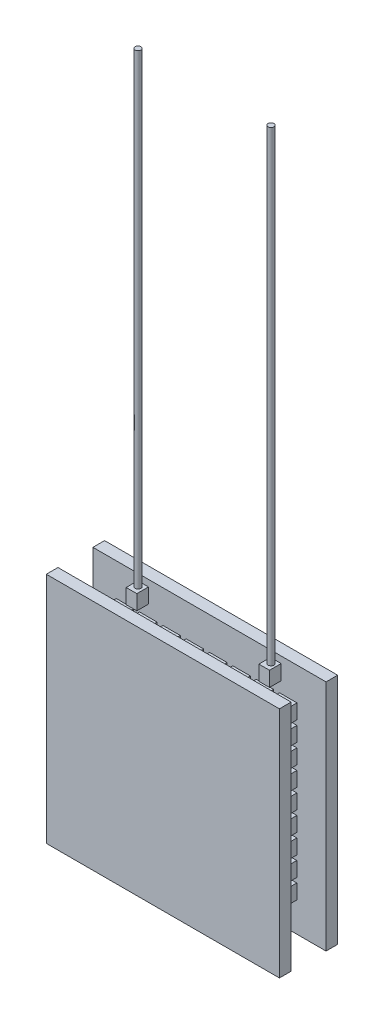
SolidWorks part; units mm, degrees
ref_plane "Front Plane" through (0, 0, 0) normal (0, 0, 1) x (1, 0, 0)
ref_plane "Top Plane" through (0, 0, 0) normal (0, 1, 0) x (1, 0, 0)
ref_plane "Right Plane" through (0, 0, 0) normal (1, 0, 0) x (0, 0, -1)
sketch "Sketch2" plane through (0, 0, 0) normal (0, 0, 1) x (1, 0, 0)
  line L0 (-3.25, 4) -> (-3.25, -4) construction
  line L1 (-5, 5) -> (5, 5)
  line L2 (-5, 5) -> (-5, -5)
  line L3 (-5, -5) -> (5, -5)
  line L4 (5, 5) -> (5, -5)
  line L5 (-5, 5) -> (5, -5) construction
  line L6 (-5, -5) -> (5, 5) construction
  line L7 (-4, 4) -> (4, 4)
  line L8 (-4, 4) -> (-4, -4)
  line L9 (-4, -4) -> (4, -4)
  line L10 (4, 4) -> (4, -4)
  line L11 (-4, 4) -> (4, -4) construction
  line L12 (-4, -4) -> (4, 4) construction
  line L13 (-3, 4) -> (-3, -4) construction
  line L14 (-2.25, 4) -> (-2.25, -4) construction
  line L15 (-2, 4) -> (-2, -4) construction
  line L16 (-1.25, 4) -> (-1.25, -4) construction
  line L17 (-1, 4) -> (-1, -4) construction
  line L18 (-0.25, 4) -> (-0.25, -4) construction
  line L19 (0, 4) -> (0, -4) construction
  line L20 (0.75, 4) -> (0.75, -4) construction
  line L21 (1, 4) -> (1, -4) construction
  line L22 (1.75, 4) -> (1.75, -4) construction
  line L23 (2, 4) -> (2, -4) construction
  line L24 (2.75, 4) -> (2.75, -4) construction
  line L25 (3, 4) -> (3, -4) construction
  line L26 (3.75, 4) -> (3.75, -4) construction
  line L27 (-4, 3.7306) -> (3.7306, 3.7306) construction
  line L28 (-4, 3.5986) -> (3.75, 3.5986) construction
  line L29 (-4, 2.7927) -> (3.75, 2.7927) construction
  line L30 (-4, 2.9681) -> (3.75, 2.9681) construction
  line L31 (-4, 2.1419) -> (3.75, 2.1419) construction
  line L32 (-4, 1.9812) -> (3.75, 1.9812) construction
  line L33 (-4, 1.3998) -> (3.75, 1.3998) construction
  line L34 (-4, 1.2019) -> (3.75, 1.2019) construction
  line L35 (-4, 0.6083) -> (3.75, 0.6083) construction
  line L36 (-4, 0.4475) -> (3.75, 0.4475) construction
  line L37 (-4, 0.3462) -> (3.75, 0.3462) construction
  line L38 (-4, -0.2996) -> (3.75, -0.2996) construction
  line L39 (-4, -0.926) -> (3.75, -0.926) construction
  line L40 (-4, -1.0978) -> (3.75, -1.0978) construction
  line L41 (-4, -1.8713) -> (3.8494, -1.8713) construction
  line L42 (-4, -2.106) -> (3.75, -2.106) construction
  line L43 (-4, -2.8245) -> (3.8494, -2.8245) construction
  line L44 (-4, -3.0005) -> (3.75, -3.0005) construction
  line L45 (-4, -5.4348) -> (3.75, -3.75) construction
  line L46 (-4, 3.5986) -> (-3.25, 3.5986)
  line L47 (-3.25, 3.5986) -> (-3.25, 2.9681)
  line L48 (-3.25, 2.9681) -> (-4, 2.9681)
  line L49 (-4, 2.7927) -> (-3.25, 2.7927)
  line L50 (-3.25, 2.7927) -> (-3.25, 2.1419)
  line L51 (-3.25, 2.1419) -> (-4, 2.1419)
  line L52 (-4, 1.9812) -> (-3.25, 1.9812)
  line L53 (-3.25, 1.9812) -> (-3.25, 1.3998)
  line L54 (-3.25, 1.3998) -> (-4, 1.3998)
  line L55 (-4, 1.2019) -> (-3.25, 1.2019)
  line L56 (-3.25, 1.2019) -> (-3.25, 0.6083)
  line L57 (-3.25, 0.6083) -> (-4, 0.6083)
  line L58 (-4, -0.2996) -> (-3.25, -0.2996)
  line L59 (-3.25, -0.2996) -> (-3.25, -0.926)
  line L60 (-3.25, -0.926) -> (-4, -0.926)
  line L61 (-4, -1.0978) -> (-3.25, -1.0978)
  line L62 (-3.25, -1.0978) -> (-3.25, -1.8713)
  line L63 (-3.25, -1.8713) -> (-4, -1.8713)
  line L64 (-4, -1.8713) -> (-4, -2.106)
  line L65 (-4, -2.106) -> (-3.25, -2.106)
  line L66 (-3.25, -2.106) -> (-3.25, -2.8245)
  line L67 (-3.25, -2.8245) -> (-4, -2.8245)
  line L68 (-4, -3.0005) -> (-3.25, -3.0005)
  line L69 (-3.25, -3.0005) -> (-3.25, -5.4348)
  line L70 (-3.25, -5.4348) -> (-4, -5.4348)
  line L71 (-3.0005, -3.0005) -> (-2.25, -3.0005)
  line L72 (-2.25, -3.0005) -> (-2.25, -3.8071)
  line L73 (-2.25, -3.8071) -> (-3, -5.2174)
  line L74 (-3, -5.2174) -> (-3.0005, -3.0005)
  line L75 (-3, -2.106) -> (-2.25, -2.106)
  line L76 (-2.25, -2.106) -> (-2.25, -2.8245)
  line L77 (-2.25, -2.8245) -> (-3, -2.8245)
  line L78 (-3, -2.8245) -> (-3, -2.106)
  line L79 (-3, -1.0978) -> (-2.25, -1.0978)
  line L80 (-2.25, -1.0978) -> (-2.25, -1.8713)
  line L81 (-2.25, -1.8713) -> (-3, -1.8713)
  line L82 (-3, -1.8713) -> (-3, -1.0978)
  line L83 (-2.25, -1.0978) -> (-2.25, -1.8713)
  line L84 (-3, -0.2996) -> (-2.25, -0.2996)
  line L85 (-2.25, -0.2996) -> (-2.25, -0.926)
  line L86 (-2.25, -0.926) -> (-3, -0.926)
  line L87 (-3, -0.926) -> (-3, -0.2996)
  line L88 (-3, 0.4475) -> (-2.25, 0.4475)
  line L89 (-2.25, 0.4475) -> (-2.25, 0.3462)
  line L90 (-2.25, 0.3462) -> (-3, 0.3462)
  line L91 (-3, 0.3462) -> (-3, 0.4475)
  line L92 (-4, 0.3462) -> (-3.25, 0.3462)
  line L93 (-3.25, 0.3462) -> (-3.25, 0.4475)
  line L94 (-3.25, 0.4475) -> (-4, 0.4475)
  line L95 (-3, 0.6083) -> (-2.25, 0.6083)
  line L96 (-2.25, 0.6083) -> (-2.25, 1.2019)
  line L97 (-2.25, 1.2019) -> (-3, 1.2019)
  line L98 (-3, 1.2019) -> (-3, 0.6083)
  line L99 (-3, 1.3998) -> (-2.25, 1.3998)
  line L100 (-2.25, 1.3998) -> (-2.25, 1.9812)
  line L101 (-2.25, 1.9812) -> (-3, 1.9812)
  line L102 (-3, 1.9812) -> (-3, 1.3998)
  line L103 (-3, 2.1419) -> (-2.25, 2.1419)
  line L104 (-2.25, 2.1419) -> (-2.25, 2.7927)
  line L105 (-2.25, 2.7927) -> (-3, 2.7927)
  line L106 (-3, 2.7927) -> (-3, 2.1419)
  line L107 (-3, 2.9681) -> (-2.25, 2.9681)
  line L108 (-2.25, 2.9681) -> (-2.25, 3.5986)
  line L109 (-2.25, 3.5986) -> (-3, 3.5986)
  line L110 (-3, 3.5986) -> (-3, 2.9681)
  line L111 (-2, 3.5986) -> (-2, 2.9681)
  line L112 (-2, 2.9681) -> (-1.25, 2.9681)
  line L113 (-1.25, 2.9681) -> (-1.25, 3.5986)
  line L114 (-1.25, 3.5986) -> (-2, 3.5986)
  line L115 (-2, 2.7927) -> (-2, 2.1419)
  line L116 (-2, 2.1419) -> (-1.25, 2.1419)
  line L117 (-1.25, 2.1419) -> (-1.25, 2.7927)
  line L118 (-1.25, 2.7927) -> (-2, 2.7927)
  line L119 (-2, 2) -> (-1.25, 1.9812)
  line L120 (-1.25, 1.9812) -> (-1.25, 1.3998)
  line L121 (-1.25, 1.3998) -> (-2, 1.3998)
  line L122 (-2, 1.3998) -> (-2, 2)
  line L123 (-2, 1.2019) -> (-1.25, 1.2019)
  line L124 (-1.25, 1.2019) -> (-1.25, 0.6083)
  line L125 (-1.25, 0.6083) -> (-2, 0.6083)
  line L126 (-2, 0.6083) -> (-2, 1.2019)
  line L127 (-2, 0.4475) -> (-1.25, 0.4475)
  line L128 (-1.25, 0.4475) -> (-1.25, 0.3462)
  line L129 (-1.25, 0.3462) -> (-2, 0.3462)
  line L130 (-2, 0.3462) -> (-2, 0.4475)
  line L131 (-2, -0.2996) -> (-1.25, -0.2996)
  line L132 (-1.25, -0.2996) -> (-1.25, -0.926)
  line L133 (-1.25, -0.926) -> (-2, -0.926)
  line L134 (-2, -0.926) -> (-2, -0.2996)
  line L135 (-2, -1.0978) -> (-1.25, -1.0978)
  line L136 (-1.25, -1.0978) -> (-1.25, -1.8713)
  line L137 (-1.25, -1.8713) -> (-2, -1.8713)
  line L138 (-2, -1.8713) -> (-2, -1.0978)
  line L139 (-2, -2.106) -> (-1.25, -2.106)
  line L140 (-1.25, -2.106) -> (-1.25, -2.8245)
  line L141 (-1.25, -2.8245) -> (-2, -2.8245)
  line L142 (-2, -2.8245) -> (-2, -2.106)
  line L143 (-2, -3.0005) -> (-1.25, -3.0005)
  line L144 (-1.25, -3.0005) -> (-1.25, -4.837)
  line L145 (-1.25, -4.837) -> (-2, -5)
  line L146 (-2, -5) -> (-2, -3.0005)
  line L147 (-1, 3.5986) -> (-0.25, 3.5986)
  line L148 (-0.25, 3.5986) -> (-0.25, 2.9681)
  line L149 (-0.25, 2.9681) -> (-1, 2.9681)
  line L150 (-1, 2.9681) -> (-1, 3.5986)
  line L151 (-1, 2.7927) -> (-0.25, 2.7927)
  line L152 (-0.25, 2.7927) -> (-0.25, 2.1419)
  line L153 (-0.25, 2.1419) -> (-1, 2.1419)
  line L154 (-1, 2.1419) -> (-1, 2.7927)
  line L155 (-1, 1.9812) -> (-0.25, 1.9812)
  line L156 (-0.25, 1.9812) -> (-0.25, 1.3998)
  line L157 (-0.25, 1.3998) -> (-1, 1.3998)
  line L158 (-1, 1.3998) -> (-1, 1.9812)
  line L159 (-1, 1.2019) -> (-0.25, 1.2019)
  line L160 (-0.25, 1.2019) -> (-0.25, 0.6083)
  line L161 (-0.25, 0.6083) -> (-1, 0.6083)
  line L162 (-1, 0.6083) -> (-1, 1.2019)
  line L163 (-1, 0.4475) -> (-0.25, 0.4475)
  line L164 (-0.25, 0.4475) -> (-0.25, 0.3462)
  line L165 (-0.25, 0.3462) -> (-1, 0.3462)
  line L166 (-1, 0.3462) -> (-1, 0.4475)
  line L167 (-1, -0.2996) -> (-0.25, -0.2996)
  line L168 (-0.25, -0.2996) -> (-0.25, -0.926)
  line L169 (-0.25, -0.926) -> (-1, -0.926)
  line L170 (-1, -0.926) -> (-1, -0.2996)
  line L171 (-1, -1.0978) -> (-0.25, -1.0978)
  line L172 (-0.25, -1.0978) -> (-0.25, -1.8713)
  line L173 (-0.25, -1.8713) -> (-1, -1.8713)
  line L174 (-1, -1.8713) -> (-1, -1.0978)
  line L175 (-1, -2.106) -> (-0.25, -2.106)
  line L176 (-0.25, -2.106) -> (-0.25, -2.8245)
  line L177 (-0.25, -2.8245) -> (-1, -2.8245)
  line L178 (-1, -2.8245) -> (-1, -2.106)
  line L179 (-1, -3.0005) -> (-0.25, -3.0005)
  line L180 (-0.25, -3.0005) -> (-0.25, -4.6196)
  line L181 (-0.25, -4.6196) -> (-1, -4.7826)
  line L182 (-1, -4.7826) -> (-1, -3.0005)
  line L183 (0, -3.0005) -> (0.75, -3.0005)
  line L184 (0.75, -3.0005) -> (0.75, -4.4022)
  line L185 (0.75, -4.4022) -> (0, -4.5652)
  line L186 (0, -4.5652) -> (0, -3.0005)
  line L187 (1, -3.0005) -> (1.75, -3.0005)
  line L188 (1.75, -3.0005) -> (1.75, -4.1848)
  line L189 (1.75, -4.1848) -> (1, -4.3478)
  line L190 (1, -4.3478) -> (1, -3.0005)
  line L191 (2, -3.0005) -> (2.75, -3.0005)
  line L192 (2.75, -3.0005) -> (2.75, -3.9674)
  line L193 (2.75, -3.9674) -> (2, -4.1304)
  line L194 (2, -4.1304) -> (2, -3.0005)
  line L195 (3, -3.0005) -> (3.75, -3.0005)
  line L196 (3.75, -3.0005) -> (3.75, -3.75)
  line L197 (3.75, -3.75) -> (3, -3.913)
  line L198 (3, -3.913) -> (3, -3.0005)
  line L199 (0, -2.106) -> (0, -2.8245)
  line L200 (0, -2.8245) -> (0.75, -2.8245)
  line L201 (0.75, -2.8245) -> (0.75, -2.106)
  line L202 (0.75, -2.106) -> (0, -2.106)
  line L203 (0, -1.8713) -> (0.75, -1.8713)
  line L204 (0.75, -1.8713) -> (0.75, -1.0978)
  line L205 (0.75, -1.0978) -> (0, -1.0978)
  line L206 (0, -1.0978) -> (0, -1.8713)
  line L207 (0, -0.926) -> (0.75, -0.926)
  line L208 (0.75, -0.926) -> (0.75, -0.2996)
  line L209 (0.75, -0.2996) -> (0, -0.2996)
  line L210 (0, -0.2996) -> (0, -0.926)
  line L211 (0, 0.3462) -> (0.75, 0.3462)
  line L212 (0.75, 0.3462) -> (0.75, 0.4475)
  line L213 (0.75, 0.4475) -> (0, 0.4475)
  line L214 (0, 0.4475) -> (0, 0.3462)
  line L215 (0, 1.2019) -> (0.75, 1.2019)
  line L216 (0.75, 1.2019) -> (0.75, 0.6083)
  line L217 (0.75, 0.6083) -> (0, 0.6083)
  line L218 (0, 0.6083) -> (0, 1.2019)
  line L219 (0, 1.3998) -> (0.75, 1.3998)
  line L220 (0.75, 1.3998) -> (0.75, 1.9812)
  line L221 (0.75, 1.9812) -> (0, 1.9812)
  line L222 (0, 1.9812) -> (0, 1.3998)
  line L223 (0, 2.1419) -> (0.75, 2.1419)
  line L224 (0.75, 2.1419) -> (0.75, 2.7927)
  line L225 (0.75, 2.7927) -> (0, 2.7927)
  line L226 (0, 2.7927) -> (0, 2.1419)
  line L227 (0, 3.5986) -> (0.75, 3.5986)
  line L228 (0.75, 3.5986) -> (0.75, 2.9681)
  line L229 (0.75, 2.9681) -> (0, 2.9681)
  line L230 (0, 2.9681) -> (0, 3.5986)
  line L231 (1, 3.5986) -> (1.75, 3.5986)
  line L232 (1.75, 3.5986) -> (1.75, 2.9681)
  line L233 (1.75, 2.9681) -> (1, 2.9681)
  line L234 (1, 2.9681) -> (1, 3.5986)
  line L235 (2, 3.5986) -> (2.75, 3.5986)
  line L236 (2.75, 3.5986) -> (2.75, 2.9681)
  line L237 (2.75, 2.9681) -> (2, 2.9681)
  line L238 (2, 2.9681) -> (2, 3.5986)
  line L239 (3, 3.5986) -> (3.75, 3.5986)
  line L240 (3.75, 3.5986) -> (3.75, 2.9681)
  line L241 (3.75, 2.9681) -> (3, 3)
  line L242 (3, 3) -> (3, 3.5986)
  line L243 (1, 2.7927) -> (1.75, 2.7927)
  line L244 (1.75, 2.7927) -> (1.75, 2.1419)
  line L245 (1.75, 2.1419) -> (1, 2.1419)
  line L246 (1, 2.1419) -> (1, 2.7927)
  line L247 (2, 2.7927) -> (2.75, 2.7927)
  line L248 (2.75, 2.7927) -> (2.75, 2.1419)
  line L249 (2.75, 2.1419) -> (2, 2.1419)
  line L250 (2, 2.1419) -> (2, 2.7927)
  line L251 (2, 1.9812) -> (2.75, 1.9812)
  line L252 (2.75, 1.9812) -> (2.75, 1.3998)
  line L253 (2.75, 1.3998) -> (2, 1.3998)
  line L254 (2, 1.9812) -> (2, 1.3998)
  line L255 (1, 1.9812) -> (1, 1.3998)
  line L256 (1, 1.3998) -> (1.75, 1.3998)
  line L257 (1.75, 1.3998) -> (1.75, 1.9812)
  line L258 (1.75, 1.9812) -> (1, 1.9812)
  line L259 (1, 1.2019) -> (1, 0.6083)
  line L260 (1, 0.6083) -> (1.75, 0.6083)
  line L261 (1.75, 0.6083) -> (1.75, 1.2019)
  line L262 (1.75, 1.2019) -> (1, 1.2019)
  line L263 (2, 1.2019) -> (2, 0.6083)
  line L264 (2, 1.2019) -> (2.75, 1.2019)
  line L265 (2.75, 1.2019) -> (2.75, 0.6083)
  line L266 (2.75, 0.6083) -> (2, 0.6083)
  line L267 (1, 0.4475) -> (1.75, 0.4475)
  line L268 (1.75, 0.4475) -> (1.75, 0.3462)
  line L269 (1.75, 0.3462) -> (1, 0.3462)
  line L270 (1, 0.3462) -> (1, 0.4475)
  line L271 (1, -0.2996) -> (1, -0.926)
  line L272 (1, -0.926) -> (1.75, -0.926)
  line L273 (1.75, -0.926) -> (1.75, -0.2996)
  line L274 (1.75, -0.2996) -> (1, -0.2996)
  line L275 (1, -1.0978) -> (1.75, -1.0978)
  line L276 (1.75, -1.0978) -> (1.75, -1.8713)
  line L277 (1.75, -1.8713) -> (1, -1.8713)
  line L278 (1, -1.8713) -> (1, -1.0978)
  line L279 (1, -2.106) -> (1, -2.8245)
  line L280 (1, -2.8245) -> (1.75, -2.8245)
  line L281 (1.75, -2.8245) -> (1.75, -2.106)
  line L282 (1.75, -2.106) -> (1, -2.106)
  line L283 (2, 0.4475) -> (2, 0.3462)
  line L284 (2, 0.3462) -> (2.75, 0.3462)
  line L285 (2.75, 0.3462) -> (2.75, 0.4475)
  line L286 (2.75, 0.4475) -> (2, 0.4475)
  line L287 (2, -0.2996) -> (2, -0.926)
  line L288 (2, -0.926) -> (2.75, -0.926)
  line L289 (2.75, -0.926) -> (2.75, -0.2996)
  line L290 (2.75, -0.2996) -> (2, -0.2996)
  point P0 (0, 0)
  point P6 (0, 0)
  dimension "D1" = 10
  dimension "D2" = 10
  dimension "D3" = 1
  dimension "D4" = 0.75
  dimension "D5" = 0.25
  dimension "D6" = 0.75
  dimension "D7" = 0.25
  dimension "D8" = 0.75
  dimension "D9" = 0.25
  dimension "D10" = 0.75
  dimension "D11" = 0.75
  dimension "D12" = 0.25
  dimension "D13" = 0.75
  dimension "D14" = 0.25
  dimension "D15" = 0.75
  dimension "D16" = 0.25
  dimension "D17" = 0.75
sketch "Sketch3" plane through (0, 0, 0) normal (0, 0, 1) x (1, 0, 0)
  line L0 (-4, 3.5986) -> (-4, 2.9681)
  line L1 (-4, 2.9681) -> (-3.25, 2.9681)
  line L2 (-3.25, 2.9681) -> (-3.25, 3.5986)
  line L3 (-3.25, 3.5986) -> (-4, 3.5986)
  line L6 (-2.2497, 3.5985) -> (-2.9997, 3.5985)
  line L7 (-2.9997, 3.5985) -> (-2.9997, 2.9679)
  line L8 (-2.9997, 2.9679) -> (-2.2497, 2.9679)
  line L9 (-2.2497, 2.9679) -> (-2.2497, 3.5985)
  line L10 (-1.2494, 3.5983) -> (-1.9994, 3.5983)
  line L11 (-1.9994, 3.5983) -> (-1.9994, 2.9677)
  line L12 (-1.9994, 2.9677) -> (-1.2494, 2.9677)
  line L13 (-1.2494, 2.9677) -> (-1.2494, 3.5983)
  line L14 (-0.2492, 3.5981) -> (-0.9992, 3.5981)
  line L15 (-0.9992, 3.5981) -> (-0.9992, 2.9675)
  line L16 (-0.9992, 2.9675) -> (-0.2492, 2.9675)
  line L17 (-0.2492, 2.9675) -> (-0.2492, 3.5981)
  line L18 (0.7511, 3.5979) -> (0.0011, 3.5979)
  line L19 (0.0011, 3.5979) -> (0.0011, 2.9673)
  line L20 (0.0011, 2.9673) -> (0.7511, 2.9673)
  line L21 (0.7511, 2.9673) -> (0.7511, 3.5979)
  line L22 (1.7514, 3.5977) -> (1.0014, 3.5977)
  line L23 (1.0014, 3.5977) -> (1.0014, 2.9671)
  line L24 (1.0014, 2.9671) -> (1.7514, 2.9671)
  line L25 (1.7514, 2.9671) -> (1.7514, 3.5977)
  line L26 (2.7517, 3.5975) -> (2.0017, 3.5975)
  line L27 (2.0017, 3.5975) -> (2.0017, 2.967)
  line L28 (2.0017, 2.967) -> (2.7517, 2.967)
  line L29 (2.7517, 2.967) -> (2.7517, 3.5975)
  line L30 (3.752, 3.5974) -> (3.002, 3.5974)
  line L31 (3.002, 3.5974) -> (3.002, 2.9668)
  line L32 (3.002, 2.9668) -> (3.752, 2.9668)
  line L33 (3.752, 2.9668) -> (3.752, 3.5974)
  line L34 (-3.2508, 2.7619) -> (-4.0008, 2.7619)
  line L35 (-4.0008, 2.7619) -> (-4.0008, 2.1313)
  line L36 (-4.0008, 2.1313) -> (-3.2508, 2.1313)
  line L37 (-3.2508, 2.1313) -> (-3.2508, 2.7619)
  line L38 (-2.2505, 2.7617) -> (-3.0005, 2.7617)
  line L39 (-3.0005, 2.7617) -> (-3.0005, 2.1312)
  line L40 (-3.0005, 2.1312) -> (-2.2505, 2.1312)
  line L41 (-2.2505, 2.1312) -> (-2.2505, 2.7617)
  line L42 (-2.0002, 2.7616) -> (-2.0002, 2.131)
  line L43 (-1.2502, 2.7616) -> (-2.0002, 2.7616)
  line L44 (-2.0002, 2.131) -> (-1.2502, 2.131)
  line L45 (-1.2502, 2.131) -> (-1.2502, 2.7616)
  line L46 (-0.9999, 2.7614) -> (-0.9999, 2.1308)
  line L47 (-0.2499, 2.7614) -> (-0.9999, 2.7614)
  line L48 (-0.9999, 2.1308) -> (-0.2499, 2.1308)
  line L49 (-0.2499, 2.1308) -> (-0.2499, 2.7614)
  line L50 (0.7504, 2.7612) -> (0.0004, 2.7612)
  line L51 (0.0004, 2.7612) -> (0.0004, 2.1306)
  line L52 (0.0004, 2.1306) -> (0.7504, 2.1306)
  line L53 (0.7504, 2.1306) -> (0.7504, 2.7612)
  line L54 (1.0006, 2.761) -> (1.0006, 2.1304)
  line L55 (1.7506, 2.761) -> (1.0006, 2.761)
  line L56 (1.0006, 2.1304) -> (1.7506, 2.1304)
  line L57 (1.7506, 2.1304) -> (1.7506, 2.761)
  line L58 (2.0009, 2.7608) -> (2.0009, 2.1302)
  line L59 (2.7509, 2.7608) -> (2.0009, 2.7608)
  line L60 (2.0009, 2.1302) -> (2.7509, 2.1302)
  line L61 (2.7509, 2.1302) -> (2.7509, 2.7608)
  line L62 (3.0012, 2.7607) -> (3.0012, 2.1301)
  line L63 (3.7512, 2.7607) -> (3.0012, 2.7607)
  line L64 (3.0012, 2.1301) -> (3.7512, 2.1301)
  line L65 (3.7512, 2.1301) -> (3.7512, 2.7607)
  line L66 (-3.2515, 1.9252) -> (-4.0015, 1.9252)
  line L67 (-4.0015, 1.9252) -> (-4.0015, 1.2946)
  line L68 (-4.0015, 1.2946) -> (-3.2515, 1.2946)
  line L69 (-3.2515, 1.2946) -> (-3.2515, 1.9252)
  line L70 (-2.2512, 1.925) -> (-3.0012, 1.925)
  line L71 (-3.0012, 1.925) -> (-3.0012, 1.2944)
  line L72 (-3.0012, 1.2944) -> (-2.2512, 1.2944)
  line L73 (-2.2512, 1.2944) -> (-2.2512, 1.925)
  line L74 (-2.001, 1.9248) -> (-2.001, 1.2943)
  line L75 (-1.251, 1.9248) -> (-2.001, 1.9248)
  line L76 (-2.001, 1.2943) -> (-1.251, 1.2943)
  line L77 (-1.251, 1.2943) -> (-1.251, 1.9248)
  line L78 (-1.0007, 1.9247) -> (-1.0007, 1.2941)
  line L79 (-0.2507, 1.9247) -> (-1.0007, 1.9247)
  line L80 (-1.0007, 1.2941) -> (-0.2507, 1.2941)
  line L81 (-0.2507, 1.2941) -> (-0.2507, 1.9247)
  line L82 (0.7496, 1.9245) -> (-0.0004, 1.9245)
  line L83 (-0.0004, 1.9245) -> (-0.0004, 1.2939)
  line L84 (-0.0004, 1.2939) -> (0.7496, 1.2939)
  line L85 (0.7496, 1.2939) -> (0.7496, 1.9245)
  line L86 (0.9999, 1.9243) -> (0.9999, 1.2937)
  line L87 (1.7499, 1.9243) -> (0.9999, 1.9243)
  line L88 (0.9999, 1.2937) -> (1.7499, 1.2937)
  line L89 (1.7499, 1.2937) -> (1.7499, 1.9243)
  line L90 (2.0002, 1.9241) -> (2.0002, 1.2935)
  line L91 (2.7502, 1.9241) -> (2.0002, 1.9241)
  line L92 (2.0002, 1.2935) -> (2.7502, 1.2935)
  line L93 (2.7502, 1.2935) -> (2.7502, 1.9241)
  line L94 (3.0004, 1.9239) -> (3.0004, 1.2933)
  line L95 (3.7504, 1.9239) -> (3.0004, 1.9239)
  line L96 (3.0004, 1.2933) -> (3.7504, 1.2933)
  line L97 (3.7504, 1.2933) -> (3.7504, 1.9239)
  line L98 (-3.2523, 1.0885) -> (-4.0023, 1.0885)
  line L99 (-4.0023, 1.0885) -> (-4.0023, 0.4579)
  line L100 (-4.0023, 0.4579) -> (-3.2523, 0.4579)
  line L101 (-3.2523, 0.4579) -> (-3.2523, 1.0885)
  line L102 (-2.252, 1.0883) -> (-3.002, 1.0883)
  line L103 (-3.002, 1.0883) -> (-3.002, 0.4577)
  line L104 (-3.002, 0.4577) -> (-2.252, 0.4577)
  line L105 (-2.252, 0.4577) -> (-2.252, 1.0883)
  line L106 (-2.0017, 1.0881) -> (-2.0017, 0.4575)
  line L107 (-1.2517, 1.0881) -> (-2.0017, 1.0881)
  line L108 (-2.0017, 0.4575) -> (-1.2517, 0.4575)
  line L109 (-1.2517, 0.4575) -> (-1.2517, 1.0881)
  line L110 (-1.0014, 1.0879) -> (-1.0014, 0.4574)
  line L111 (-0.2514, 1.0879) -> (-1.0014, 1.0879)
  line L112 (-1.0014, 0.4574) -> (-0.2514, 0.4574)
  line L113 (-0.2514, 0.4574) -> (-0.2514, 1.0879)
  line L114 (0.7488, 1.0878) -> (-0.0012, 1.0878)
  line L115 (-0.0012, 1.0878) -> (-0.0012, 0.4572)
  line L116 (-0.0012, 0.4572) -> (0.7488, 0.4572)
  line L117 (0.7488, 0.4572) -> (0.7488, 1.0878)
  line L118 (0.9991, 1.0876) -> (0.9991, 0.457)
  line L119 (1.7491, 1.0876) -> (0.9991, 1.0876)
  line L120 (0.9991, 0.457) -> (1.7491, 0.457)
  line L121 (1.7491, 0.457) -> (1.7491, 1.0876)
  line L122 (1.9994, 1.0874) -> (1.9994, 0.4568)
  line L123 (2.7494, 1.0874) -> (1.9994, 1.0874)
  line L124 (1.9994, 0.4568) -> (2.7494, 0.4568)
  line L125 (2.7494, 0.4568) -> (2.7494, 1.0874)
  line L126 (2.9997, 1.0872) -> (2.9997, 0.4566)
  line L127 (3.7497, 1.0872) -> (2.9997, 1.0872)
  line L128 (2.9997, 0.4566) -> (3.7497, 0.4566)
  line L129 (3.7497, 0.4566) -> (3.7497, 1.0872)
  line L130 (-3.253, 0.2518) -> (-4.003, 0.2518)
  line L131 (-4.003, 0.2518) -> (-4.003, -0.3788)
  line L132 (-4.003, -0.3788) -> (-3.253, -0.3788)
  line L133 (-3.253, -0.3788) -> (-3.253, 0.2518)
  line L134 (-2.2528, 0.2516) -> (-3.0028, 0.2516)
  line L135 (-3.0028, 0.2516) -> (-3.0028, -0.379)
  line L136 (-3.0028, -0.379) -> (-2.2528, -0.379)
  line L137 (-2.2528, -0.379) -> (-2.2528, 0.2516)
  line L138 (-2.0025, 0.2514) -> (-2.0025, -0.3792)
  line L139 (-1.2525, 0.2514) -> (-2.0025, 0.2514)
  line L140 (-2.0025, -0.3792) -> (-1.2525, -0.3792)
  line L141 (-1.2525, -0.3792) -> (-1.2525, 0.2514)
  line L142 (-1.0022, 0.2512) -> (-1.0022, -0.3794)
  line L143 (-0.2522, 0.2512) -> (-1.0022, 0.2512)
  line L144 (-1.0022, -0.3794) -> (-0.2522, -0.3794)
  line L145 (-0.2522, -0.3794) -> (-0.2522, 0.2512)
  line L146 (0.7481, 0.251) -> (-0.0019, 0.251)
  line L147 (-0.0019, 0.251) -> (-0.0019, -0.3795)
  line L148 (-0.0019, -0.3795) -> (0.7481, -0.3795)
  line L149 (0.7481, -0.3795) -> (0.7481, 0.251)
  line L150 (0.9984, 0.2509) -> (0.9984, -0.3797)
  line L151 (1.7484, 0.2509) -> (0.9984, 0.2509)
  line L152 (0.9984, -0.3797) -> (1.7484, -0.3797)
  line L153 (1.7484, -0.3797) -> (1.7484, 0.2509)
  line L154 (1.9986, 0.2507) -> (1.9986, -0.3799)
  line L155 (2.7486, 0.2507) -> (1.9986, 0.2507)
  line L156 (1.9986, -0.3799) -> (2.7486, -0.3799)
  line L157 (2.7486, -0.3799) -> (2.7486, 0.2507)
  line L158 (2.9989, 0.2505) -> (2.9989, -0.3801)
  line L159 (3.7489, 0.2505) -> (2.9989, 0.2505)
  line L160 (2.9989, -0.3801) -> (3.7489, -0.3801)
  line L161 (3.7489, -0.3801) -> (3.7489, 0.2505)
  line L162 (-3.2538, -0.5849) -> (-4.0038, -0.5849)
  line L163 (-4.0038, -0.5849) -> (-4.0038, -1.2155)
  line L164 (-4.0038, -1.2155) -> (-3.2538, -1.2155)
  line L165 (-3.2538, -1.2155) -> (-3.2538, -0.5849)
  line L166 (-2.2535, -0.5851) -> (-3.0035, -0.5851)
  line L167 (-3.0035, -0.5851) -> (-3.0035, -1.2157)
  line L168 (-3.0035, -1.2157) -> (-2.2535, -1.2157)
  line L169 (-2.2535, -1.2157) -> (-2.2535, -0.5851)
  line L170 (-2.0032, -0.5853) -> (-2.0032, -1.2159)
  line L171 (-1.2532, -0.5853) -> (-2.0032, -0.5853)
  line L172 (-2.0032, -1.2159) -> (-1.2532, -1.2159)
  line L173 (-1.2532, -1.2159) -> (-1.2532, -0.5853)
  line L174 (-1.003, -0.5855) -> (-1.003, -1.2161)
  line L175 (-0.253, -0.5855) -> (-1.003, -0.5855)
  line L176 (-1.003, -1.2161) -> (-0.253, -1.2161)
  line L177 (-0.253, -1.2161) -> (-0.253, -0.5855)
  line L178 (0.7473, -0.5857) -> (-0.0027, -0.5857)
  line L179 (-0.0027, -0.5857) -> (-0.0027, -1.2163)
  line L180 (-0.0027, -1.2163) -> (0.7473, -1.2163)
  line L181 (0.7473, -1.2163) -> (0.7473, -0.5857)
  line L182 (0.9976, -0.5859) -> (0.9976, -1.2164)
  line L183 (1.7476, -0.5859) -> (0.9976, -0.5859)
  line L184 (0.9976, -1.2164) -> (1.7476, -1.2164)
  line L185 (1.7476, -1.2164) -> (1.7476, -0.5859)
  line L186 (1.9979, -0.586) -> (1.9979, -1.2166)
  line L187 (2.7479, -0.586) -> (1.9979, -0.586)
  line L188 (1.9979, -1.2166) -> (2.7479, -1.2166)
  line L189 (2.7479, -1.2166) -> (2.7479, -0.586)
  line L190 (2.9982, -0.5862) -> (2.9982, -1.2168)
  line L191 (3.7482, -0.5862) -> (2.9982, -0.5862)
  line L192 (2.9982, -1.2168) -> (3.7482, -1.2168)
  line L193 (3.7482, -1.2168) -> (3.7482, -0.5862)
  line L194 (-3.2546, -1.4217) -> (-4.0046, -1.4217)
  line L195 (-4.0046, -1.4217) -> (-4.0046, -2.0523)
  line L196 (-4.0046, -2.0523) -> (-3.2546, -2.0523)
  line L197 (-3.2546, -2.0523) -> (-3.2546, -1.4217)
  line L198 (-2.2543, -1.4218) -> (-3.0043, -1.4218)
  line L199 (-3.0043, -1.4218) -> (-3.0043, -2.0524)
  line L200 (-3.0043, -2.0524) -> (-2.2543, -2.0524)
  line L201 (-2.2543, -2.0524) -> (-2.2543, -1.4218)
  line L202 (-2.004, -1.422) -> (-2.004, -2.0526)
  line L203 (-1.254, -1.422) -> (-2.004, -1.422)
  line L204 (-2.004, -2.0526) -> (-1.254, -2.0526)
  line L205 (-1.254, -2.0526) -> (-1.254, -1.422)
  line L206 (-1.0037, -1.4222) -> (-1.0037, -2.0528)
  line L207 (-0.2537, -1.4222) -> (-1.0037, -1.4222)
  line L208 (-1.0037, -2.0528) -> (-0.2537, -2.0528)
  line L209 (-0.2537, -2.0528) -> (-0.2537, -1.4222)
  line L210 (0.7466, -1.4224) -> (-0.0034, -1.4224)
  line L211 (-0.0034, -1.4224) -> (-0.0034, -2.053)
  line L212 (-0.0034, -2.053) -> (0.7466, -2.053)
  line L213 (0.7466, -2.053) -> (0.7466, -1.4224)
  line L214 (0.9968, -1.4226) -> (0.9968, -2.0532)
  line L215 (1.7468, -1.4226) -> (0.9968, -1.4226)
  line L216 (0.9968, -2.0532) -> (1.7468, -2.0532)
  line L217 (1.7468, -2.0532) -> (1.7468, -1.4226)
  line L218 (1.9971, -1.4228) -> (1.9971, -2.0533)
  line L219 (2.7471, -1.4228) -> (1.9971, -1.4228)
  line L220 (1.9971, -2.0533) -> (2.7471, -2.0533)
  line L221 (2.7471, -2.0533) -> (2.7471, -1.4228)
  line L222 (2.9974, -1.4229) -> (2.9974, -2.0535)
  line L223 (3.7474, -1.4229) -> (2.9974, -1.4229)
  line L224 (2.9974, -2.0535) -> (3.7474, -2.0535)
  line L225 (3.7474, -2.0535) -> (3.7474, -1.4229)
  line L226 (-3.2553, -2.2584) -> (-4.0053, -2.2584)
  line L227 (-4.0053, -2.2584) -> (-4.0053, -2.889)
  line L228 (-4.0053, -2.889) -> (-3.2553, -2.889)
  line L229 (-3.2553, -2.889) -> (-3.2553, -2.2584)
  line L230 (-2.255, -2.2586) -> (-3.005, -2.2586)
  line L231 (-3.005, -2.2586) -> (-3.005, -2.8891)
  line L232 (-3.005, -2.8891) -> (-2.255, -2.8891)
  line L233 (-2.255, -2.8891) -> (-2.255, -2.2586)
  line L234 (-2.0048, -2.2587) -> (-2.0048, -2.8893)
  line L235 (-1.2548, -2.2587) -> (-2.0048, -2.2587)
  line L236 (-2.0048, -2.8893) -> (-1.2548, -2.8893)
  line L237 (-1.2548, -2.8893) -> (-1.2548, -2.2587)
  line L238 (-1.0045, -2.2589) -> (-1.0045, -2.8895)
  line L239 (-0.2545, -2.2589) -> (-1.0045, -2.2589)
  line L240 (-1.0045, -2.8895) -> (-0.2545, -2.8895)
  line L241 (-0.2545, -2.8895) -> (-0.2545, -2.2589)
  line L242 (0.7458, -2.2591) -> (-0.0042, -2.2591)
  line L243 (-0.0042, -2.2591) -> (-0.0042, -2.8897)
  line L244 (-0.0042, -2.8897) -> (0.7458, -2.8897)
  line L245 (0.7458, -2.8897) -> (0.7458, -2.2591)
  line L246 (0.9961, -2.2593) -> (0.9961, -2.8899)
  line L247 (1.7461, -2.2593) -> (0.9961, -2.2593)
  line L248 (0.9961, -2.8899) -> (1.7461, -2.8899)
  line L249 (1.7461, -2.8899) -> (1.7461, -2.2593)
  line L250 (1.9963, -2.2595) -> (1.9963, -2.8901)
  line L251 (2.7463, -2.2595) -> (1.9963, -2.2595)
  line L252 (1.9963, -2.8901) -> (2.7463, -2.8901)
  line L253 (2.7463, -2.8901) -> (2.7463, -2.2595)
  line L254 (2.9966, -2.2597) -> (2.9966, -2.8902)
  line L255 (3.7466, -2.2597) -> (2.9966, -2.2597)
  line L256 (2.9966, -2.8902) -> (3.7466, -2.8902)
  line L257 (3.7466, -2.8902) -> (3.7466, -2.2597)
  line L258 (-3.2561, -3.0951) -> (-4.0061, -3.0951)
  line L259 (-4.0061, -3.0951) -> (-4.0061, -3.7257)
  line L260 (-4.0061, -3.7257) -> (-3.2561, -3.7257)
  line L261 (-3.2561, -3.7257) -> (-3.2561, -3.0951)
  line L262 (-2.2558, -3.0953) -> (-3.0058, -3.0953)
  line L263 (-3.0058, -3.0953) -> (-3.0058, -3.7259)
  line L264 (-3.0058, -3.7259) -> (-2.2558, -3.7259)
  line L265 (-2.2558, -3.7259) -> (-2.2558, -3.0953)
  line L266 (-2.0055, -3.0955) -> (-2.0055, -3.726)
  line L267 (-1.2555, -3.0955) -> (-2.0055, -3.0955)
  line L268 (-2.0055, -3.726) -> (-1.2555, -3.726)
  line L269 (-1.2555, -3.726) -> (-1.2555, -3.0955)
  line L270 (-1.0053, -3.0956) -> (-1.0053, -3.7262)
  line L271 (-0.2553, -3.0956) -> (-1.0053, -3.0956)
  line L272 (-1.0053, -3.7262) -> (-0.2553, -3.7262)
  line L273 (-0.2553, -3.7262) -> (-0.2553, -3.0956)
  line L274 (0.745, -3.0958) -> (-0.005, -3.0958)
  line L275 (-0.005, -3.0958) -> (-0.005, -3.7264)
  line L276 (-0.005, -3.7264) -> (0.745, -3.7264)
  line L277 (0.745, -3.7264) -> (0.745, -3.0958)
  line L278 (0.9953, -3.096) -> (0.9953, -3.7266)
  line L279 (1.7453, -3.096) -> (0.9953, -3.096)
  line L280 (0.9953, -3.7266) -> (1.7453, -3.7266)
  line L281 (1.7453, -3.7266) -> (1.7453, -3.096)
  line L282 (1.9956, -3.0962) -> (1.9956, -3.7268)
  line L283 (2.7456, -3.0962) -> (1.9956, -3.0962)
  line L284 (1.9956, -3.7268) -> (2.7456, -3.7268)
  line L285 (2.7456, -3.7268) -> (2.7456, -3.0962)
  line L286 (2.9959, -3.0964) -> (2.9959, -3.727)
  line L287 (3.7459, -3.0964) -> (2.9959, -3.0964)
  line L288 (2.9959, -3.727) -> (3.7459, -3.727)
  line L289 (3.7459, -3.727) -> (3.7459, -3.0964)
  dimension "D1" = 8
  dimension "D2" = 9
extrude "Boss-Extrude1" add sketch "Sketch3" along normal blind 2
extrude "Boss-Extrude2" add sketch "Sketch2" against normal blind 0.5 contours L2 L3 L4 L1
ref_plane "Plane1" through (0, 0, 0.75) normal (0, 0, -1) x (-1, 0, 0)
mirror "Mirror1" about plane through (0, 0, 0.75) normal (0, 0, -1) of "Boss-Extrude2"
sketch "Sketch4" plane through (0, 0, 0) normal (0, 0, 1) x (1, 0, 0)
  line L1 (-3.0748, 4.7207) -> (-2.6176, 4.7207)
  line L2 (-3.0748, 4.7207) -> (-3.0748, 4.0806)
  line L3 (-3.0748, 4.0806) -> (-2.6176, 4.0806)
  line L4 (-2.6176, 4.7207) -> (-2.6176, 4.0806)
  line L5 (-3.0748, 4.7207) -> (-2.6176, 4.0806) construction
  line L6 (-3.0748, 4.0806) -> (-2.6176, 4.7207) construction
  point P0 (-2.8462, 4.4007)
extrude "Boss-Extrude3" add sketch "Sketch4" along normal blind 0.5
ref_plane "Plane2" through (0, 0, 0) normal (-1, 0, 0) x (0, 0, 1)
mirror "Mirror2" about plane through (0, 0, 0) normal (-1, 0, 0) of "Boss-Extrude3"
sketch "Sketch5" plane through (0, 4.7207, 0) normal (0, 1, 0) x (1, 0, 0)
  circle A0 centre (2.8564, -0.217) radius 0.125
  circle A1 centre (-2.8466, -0.217) radius 0.125
  dimension "D1" = 0.25
  dimension "D2" = 0.25
extrude "Boss-Extrude4" add sketch "Sketch5" along normal blind 20
